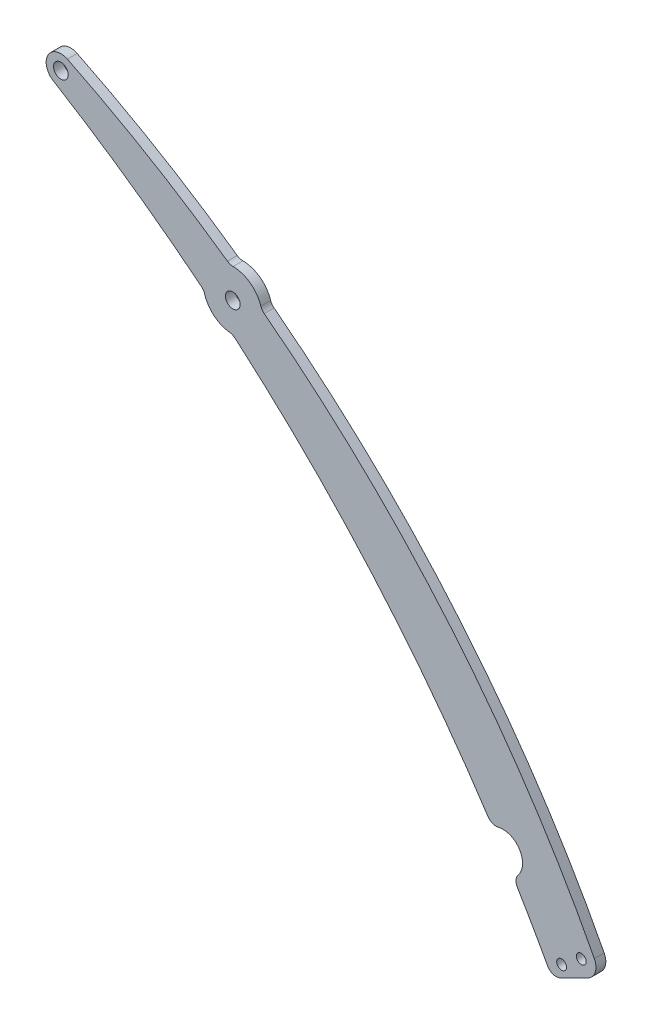
SolidWorks part; units mm, degrees
ref_plane "前视基准面" through (0, 0, 0) normal (0, 0, 1) x (1, 0, 0)
ref_plane "上视基准面" through (0, 0, 0) normal (0, 1, 0) x (1, 0, 0)
ref_plane "右视基准面" through (0, 0, 0) normal (1, 0, 0) x (0, 0, -1)
sketch "草图1" plane through (0, 0, 0) normal (0, 0, 1) x (1, 0, 0)
  line L0 (107.3025, -106.33) -> (101.7379, -109.1266)
  circle A0 centre (0, 0) radius 1.5
  arc A1 (1.322, 2.693) -> (-1.5587, -2.5633) centre (0, 0) ccw
  arc A2 (1.322, 2.693) -> (33.9065, -16.6345) centre (-104.4416, -212.7462) cw
  arc A3 (-1.5587, -2.5633) -> (28.5891, -23.732) centre (-147.0384, -241.8031) cw
  arc A4 (99.0818, -108.2932) -> (101.7379, -109.1266) centre (100.8398, -107.3396) ccw
  arc A5 (108.6186, -102.2685) -> (107.3025, -106.33) centre (105.9554, -103.6495) cw
  circle A6 centre (105.9554, -103.6495) radius 1
  circle A8 centre (101.9554, -106.6495) radius 1
  arc A9 (89.0821, -88.8702) -> (93.1109, -95.2778) centre (90, -92.7634) cw
  arc A10 (92.9522, -97.5653) -> (99.0818, -108.2932) centre (-147.0384, -241.8031) cw
  arc A11 (93.1109, -95.2778) -> (92.9522, -97.5653) centre (94.6664, -96.535) ccw
  arc A12 (89.0821, -88.8702) -> (86.9518, -88.022) centre (88.6231, -86.9235) cw
  arc A13 (29.251, -24.7173) -> (34.3572, -28.9655) centre (35, -23) ccw
  circle A14 centre (35, -23) radius 1.5
  arc A15 (41.4016, -22.1425) -> (108.6186, -102.2685) centre (-104.4416, -212.7462) cw
  arc A16 (35.4464, -29.4371) -> (86.9518, -88.022) centre (-147.0384, -241.8031) cw
  arc A17 (40.7127, -21.1656) -> (35.0445, -17.0002) centre (35, -23) ccw
  arc A18 (28.5891, -23.732) -> (29.251, -24.7173) centre (27.3347, -25.2897) cw
  arc A19 (35.4464, -29.4371) -> (34.3572, -28.9655) centre (34.1429, -30.954) ccw
  arc A20 (41.4016, -22.1425) -> (40.7127, -21.1656) centre (42.617, -20.5542) cw
  arc A21 (33.9065, -16.6345) -> (35.0445, -17.0002) centre (35.0594, -15.0002) ccw
  point P17 (92.1049, -96.1648)
  point P20 (100, -110)
  point P23 (110, -104.9743)
  point P38 (40.8647, -21.7329)
  dimension "D1" = 3
  dimension "D2" = 3
  dimension "D3" = 240
  dimension "D4" = 280
  dimension "D8" = 2
  dimension "D9" = 3
  dimension "D10" = 2
  dimension "D11" = 4
  dimension "D12" = 3
  dimension "D13" = 4
  dimension "D15" = 2
  dimension "D16" = 12
  dimension "D17" = 3
  dimension "D19" = 23
  dimension "D20" = 2
  dimension "D5" = 100
  dimension "D6" = 110
  dimension "D7" = 110
  dimension "D14" = 90
  dimension "D18" = 35
extrude "凸台-拉伸1" add sketch "草图1" along normal blind 2
move or copy body "实体-移动/复制1" [suppressed] bodies to move or copy 106 parameters "D1"=0, "D2"=0, "D3"=0
move or copy body "实体-移动/复制2" [suppressed] bodies to move or copy 107 parameters "D1"=0, "D2"=0, "D3"=0
move or copy body "实体-移动/复制3" [suppressed] bodies to move or copy 108 parameters "D1"=0, "D2"=0, "D3"=0
